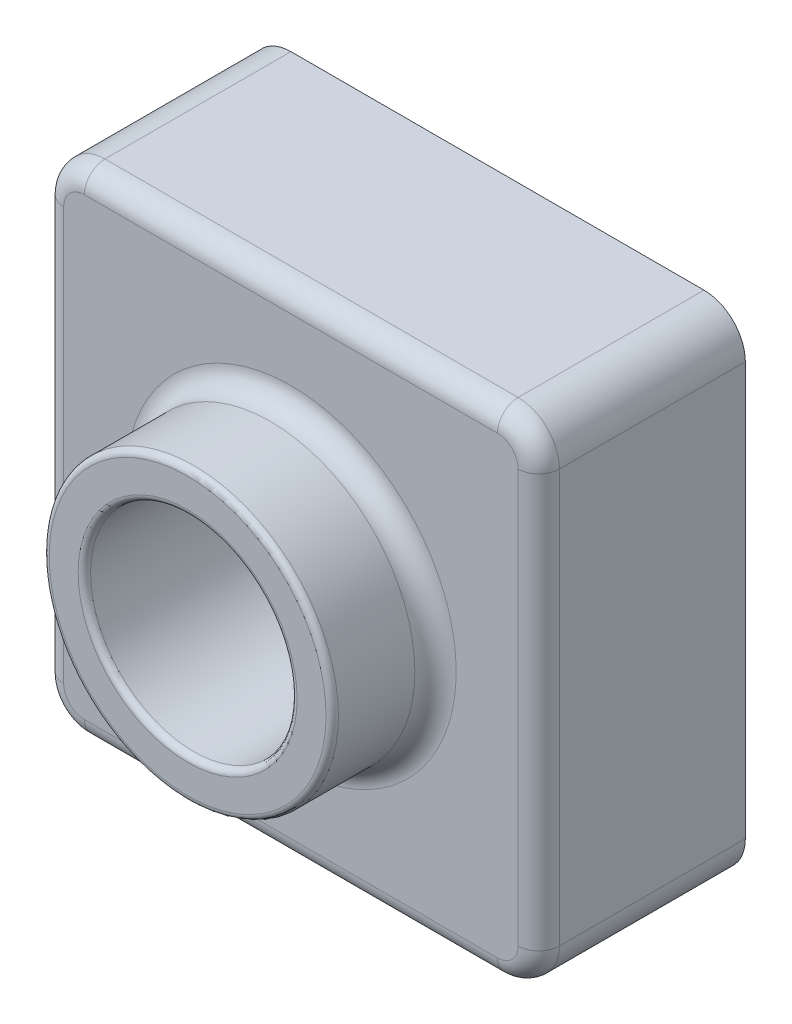
SolidWorks part; units mm, degrees
ref_plane "Front" through (0, 0, 0) normal (0, 0, 1) x (1, 0, 0)
ref_plane "Top" through (0, 0, 0) normal (0, 1, 0) x (1, 0, 0)
ref_plane "Right" through (0, 0, 0) normal (1, 0, 0) x (0, 0, -1)
other "Configuration Table"
sketch "Sketch1" plane through (0, 0, 0) normal (0, 0, 1) x (1, 0, 0)
  line L1 (0, 0) -> (120, 0)
  line L2 (0, 0) -> (0, 120)
  line L3 (0, 120) -> (120, 120)
  line L4 (120, 0) -> (120, 120)
  dimension "D1" = 120
  dimension "D2" = 120
extrude "Boss-Extrude1" add sketch "Sketch1" along normal blind 50
sketch "Sketch2" plane through (0, 0, 50) normal (0, 0, 1) x (1, 0, 0)
  line L0 (120, 120) -> (0, 120) construction
  line L1 (120, 0) -> (120, 120) construction
  circle A0 centre (60, 60) radius 35
  dimension "D1" = 70
  dimension "D2" = 60
  dimension "D3" = 60
extrude "Boss-Extrude2" add sketch "Sketch2" along normal blind 25
sketch "Sketch3" plane through (0, 0, 75) normal (0, 0, 1) x (1, 0, 0)
  circle A0 centre (60, 60) radius 25
  dimension "D1" = 50
extrude "Cut-Extrude1" cut sketch "Sketch3" against normal through all
fillet "Fillet1" radius 10 4 edges at (0, 0, 25) (120, 0, 25) (0, 120, 25) (120, 120, 25)
fillet "Fillet2" radius 1.5 2 edges at (95, 60, 75) (85, 60, 75)
fillet "Fillet3" radius 5 9 edges at (25, 60, 50) (2.9289, 117.0711, 50) (60, 120, 50) (117.0711, 117.0711, 50) (120, 60, 50) (117.0711, 2.9289, 50) (60, 0, 50) (2.9289, 2.9289, 50) (0, 60, 50)
shell "Shell1" thickness 2
